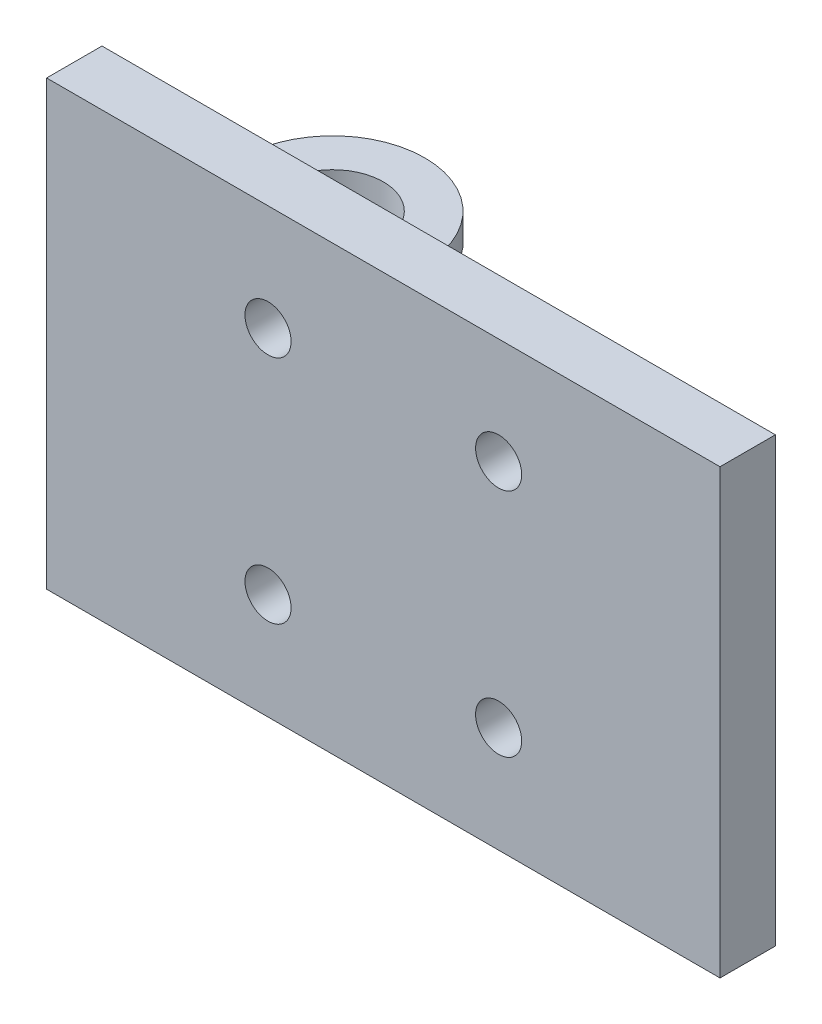
SolidWorks part; units mm, degrees
ref_plane "前视基准面" through (0, 0, 0) normal (0, 0, 1) x (1, 0, 0)
ref_plane "上视基准面" through (0, 0, 0) normal (0, 1, 0) x (1, 0, 0)
ref_plane "右视基准面" through (0, 0, 0) normal (1, 0, 0) x (0, 0, -1)
sketch "草图1" plane through (0, 0, 0) normal (0, 0, 1) x (1, 0, 0)
  line L0 (-12.5, 12.5) -> (-12.5, -12.5) construction
  line L1 (36.5, -24) -> (-36.5, -24)
  line L2 (36.5, -24) -> (36.5, 24)
  line L3 (36.5, 24) -> (-36.5, 24)
  line L4 (-36.5, -24) -> (-36.5, 24)
  line L5 (36.5, -24) -> (-36.5, 24) construction
  line L6 (36.5, 24) -> (-36.5, -24) construction
  line L7 (-12.5, -12.5) -> (12.5, -12.5) construction
  line L8 (12.5, -12.5) -> (12.5, 12.5) construction
  line L9 (12.5, 12.5) -> (-12.5, 12.5) construction
  line L10 (0, 0) -> (0, 12.5) construction
  line L11 (0, 0) -> (12.5, 0) construction
  circle A0 centre (-12.5, 12.5) radius 2.5
  circle A1 centre (12.5, 12.5) radius 2.5
  circle A2 centre (12.5, -12.5) radius 2.5
  circle A3 centre (-12.5, -12.5) radius 2.5
  dimension "D5" = 5
  dimension "D1" = 48
  dimension "D2" = 73
  dimension "D3" = 25
  dimension "D4" = 25
extrude "凸台-拉伸1" add sketch "草图1" along normal blind 6
sketch "草图3" plane through (0, 0, 0) normal (0, 1, 0) x (1, 0, 0)
  line L0 (-36.5, 0) -> (-16.5, 0)
  line L1 (36.5, 0) -> (-36.5, 0) construction
  line L2 (-16.5, 0) -> (-16.5, 15)
  line L3 (-36.5, 0) -> (-36.5, 15)
  arc A0 (-16.5, 15) -> (-36.5, 15) centre (-26.5, 15) ccw
  circle A1 centre (-26.5, 15) radius 5.5
  dimension "D3" = 11
  dimension "D1" = 20
  dimension "D2" = 15
extrude "凸台-拉伸2" add sketch "草图3" along normal blind 3 from offset 3 separate body
mirror "镜向1" about plane through (0, 0, 0) normal (0, 1, 0) of bodies 107
scale "缩放比例1" bodies to scale 108 107 106 scale about origin uniform scaling yes scale factor 0.3
